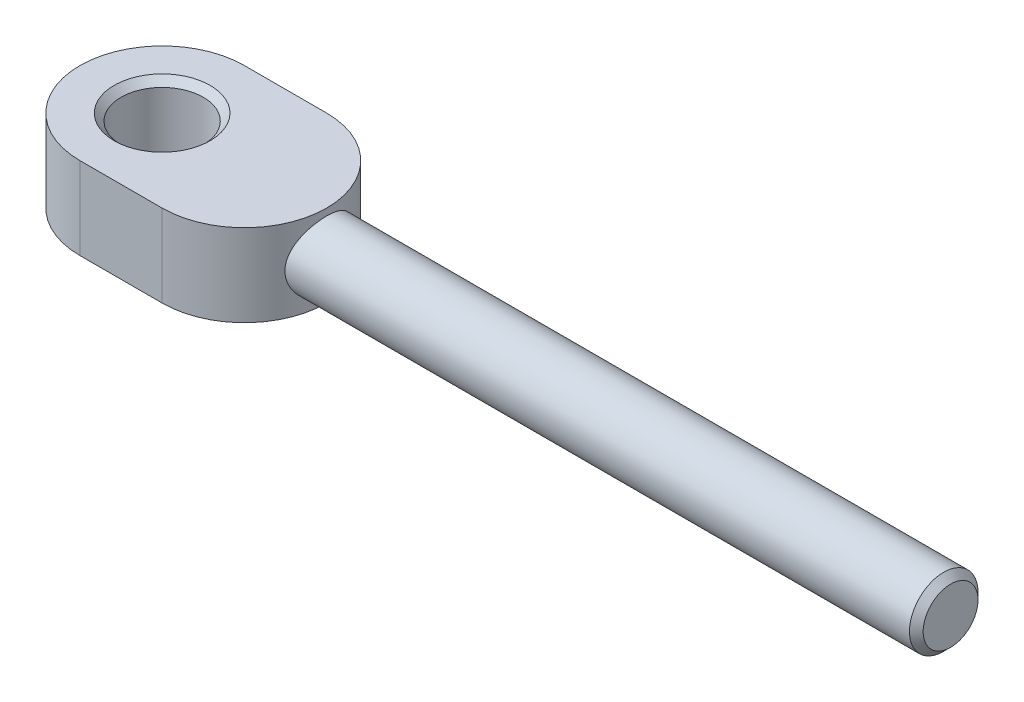
SolidWorks part; units mm, degrees
ref_plane "Front Plane" through (0, 0, 0) normal (0, 0, 1) x (1, 0, 0)
ref_plane "Top Plane" through (0, 0, 0) normal (0, 1, 0) x (1, 0, 0)
ref_plane "Right Plane" through (0, 0, 0) normal (1, 0, 0) x (0, 0, -1)
sketch "Sketch1" plane through (0, 0, 0) normal (0, 1, 0) x (1, 0, 0)
  line L0 (0, 0) -> (12, 0) construction
  line L2 (0, 12) -> (12, 12)
  line L3 (0, -12) -> (12, -12)
  arc A0 (0, 12) -> (0, -12) centre (0, 0) ccw
  arc A1 (12, -12) -> (12, 12) centre (12, 0) ccw
  circle A2 centre (0, 0) radius 6
  point P5 (6, 0)
  dimension "D3" = 12
  dimension "D1" = 12
  dimension "D2" = 12
extrude "Boss-Extrude1" add sketch "Sketch1" along normal blind 12
chamfer "Chamfer1" distance 1 angle 45 2 edges at (0, 0, 6) (0, 12, 6)
ref_plane "Plane1" through (24, 0, 0) normal (1, 0, 0) x (0, 0, -1)
sketch "Sketch2" plane through (24, 0, 0) normal (1, 0, 0) x (0, 0, -1)
  line L0 (12, 12) -> (-12, 12) construction
  line L1 (12, 12) -> (-12, 12)
  line L2 (-12, 0) -> (12, 0) construction
  line L3 (-12, 0) -> (12, 0)
  line L4 (12, 12) -> (4.4721, 8.2361)
  line L5 (-12, 12) -> (-4.4721, 8.2361)
  line L6 (4.4721, 3.7639) -> (12, 0)
  line L7 (-4.4721, 3.7639) -> (-12, 0)
  line L8 (-12, 12) -> (-12, 0) construction
  circle A0 centre (0, 6) radius 5
  dimension "D1" = 10
  dimension "D2" = 12
extrude "Boss-Extrude2" add sketch "Sketch2" along normal blind 91 and the other way blind 3 contours A0
chamfer "Chamfer2" distance 1 angle 45 1 edges at (115, 6, -5)
